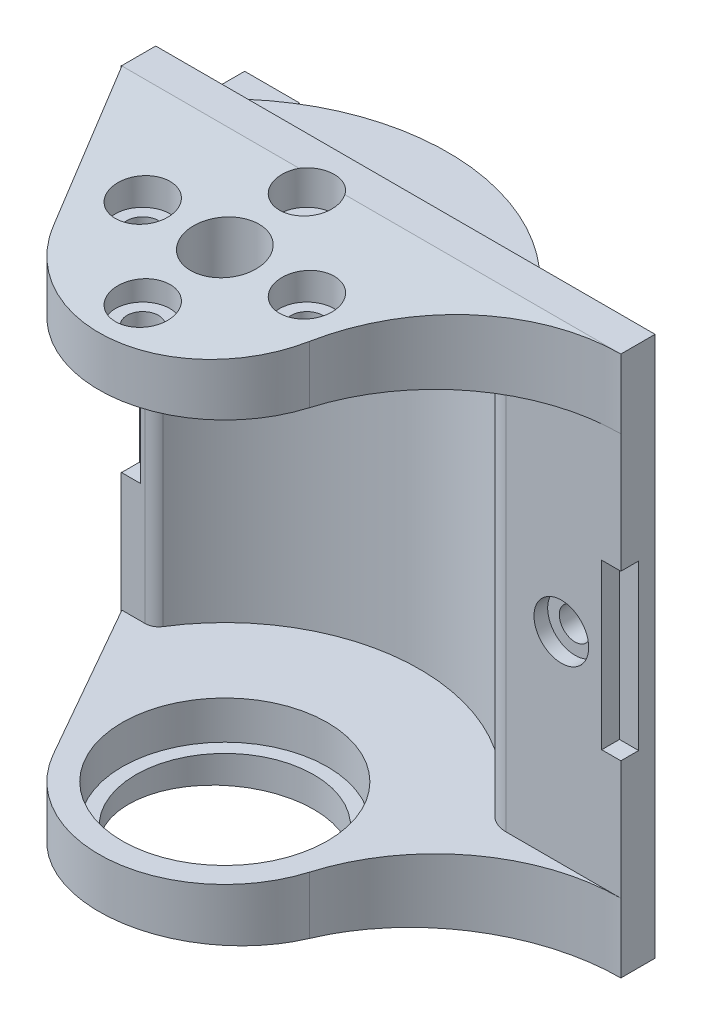
SolidWorks part; units mm, degrees
ref_plane "前视基准面" through (0, 0, 0) normal (0, 0, 1) x (1, 0, 0)
ref_plane "上视基准面" through (0, 0, 0) normal (0, 1, 0) x (1, 0, 0)
ref_plane "右视基准面" through (0, 0, 0) normal (1, 0, 0) x (0, 0, -1)
sketch "草图1" plane through (0, 0, 0) normal (0, 1, 0) x (1, 0, 0)
  circle A1 centre (0, 0) radius 16.3
  dimension "D1" = 32.6
extrude "凸台-拉伸1" add sketch "草图1" along normal mid plane 39.5
sketch "草图2" plane through (0, -19.75, 0) normal (0, -1, 0) x (1, 0, 0)
  line L1 (-14.65, -7.1) -> (21.85, -7.1)
  line L2 (-14.65, -7.1) -> (-14.65, -9.6)
  line L3 (-14.65, -9.6) -> (21.85, -9.6)
  line L4 (21.85, -7.1) -> (21.85, -9.6)
  dimension "D1" = 2.5
  dimension "D2" = 9.6
  dimension "D3" = 36.5
  dimension "D4" = 14.65
extrude "凸台-拉伸2" add sketch "草图2" against normal through all
sketch "草图3" plane through (0, -19.75, 0) normal (0, -1, 0) x (1, 0, 0)
  line L1 (21.85, -7.1) -> (-22.9944, -7.1)
  line L2 (21.85, -7.1) -> (21.85, 18.4067)
  line L3 (21.85, 18.4067) -> (-22.9944, 18.4067)
  line L4 (-22.9944, -7.1) -> (-22.9944, 18.4067)
extrude "切除-拉伸1" cut sketch "草图3" against normal blind 50
sketch "草图4" plane through (0, -19.75, 0) normal (0, -1, 0) x (1, 0, 0)
  line L0 (-14.65, -7.1462) -> (-7.9965, 4.5492)
  line L1 (21.85, -7.1) -> (21.85, 7.9567) construction
  line L2 (-14.65, -7.1462) -> (21.85, -7.1)
  arc A0 (8.8187, 2.6213) -> (-7.9965, 4.5492) centre (0, 0) ccw
  arc A1 (8.8187, 2.6213) -> (21.85, -7.1) centre (21.85, 6.4949) ccw
  dimension "D1" = 18.4
extrude "凸台-拉伸3" add sketch "草图4" against normal blind 5.05
mirror "镜向1" about plane through (0, 0, 0) normal (0, 1, 0) of "凸台-拉伸3"
sketch "草图5" plane through (0, -14.7, 0) normal (0, 1, 0) x (1, 0, 0)
  circle A0 centre (0, 0) radius 14.25
  dimension "D1" = 28.5
extrude "切除-拉伸2" cut sketch "草图5" along normal up to surface (29.4 mm away) up to face at (1.768, 14.7, -0.9093)
sketch "草图6" plane through (0, -14.7, 0) normal (0, 1, 0) x (1, 0, 0)
  circle A0 centre (0, 0) radius 7.5
  dimension "D1" = 15
extrude "切除-拉伸3" cut sketch "草图6" against normal through all
sketch "草图8" plane through (0, 19.75, 0) normal (0, 1, 0) x (1, 0, 0)
  circle A0 centre (0, -6) radius 1.15
  dimension "D1" = 2.3
  dimension "D2" = 6
extrude "切除-拉伸5" cut sketch "草图8" against normal up to surface (5.05 mm away) up to face at (1.1787, 14.7, -4.1645)
pattern_circular "阵列(圆周)1" count 4 over 360 about axis through (0, 0, 0) along (0, 1, 0) of "切除-拉伸5"
sketch "草图9" plane through (0, 19.75, 0) normal (0, 1, 0) x (1, 0, 0)
  circle A0 centre (0, 0) radius 2.5
  dimension "D1" = 5
extrude "切除-拉伸6" cut sketch "草图9" against normal up to next
sketch "草图10" plane through (0, 19.75, 0) normal (0, 1, 0) x (1, 0, 0)
  circle A0 centre (0, 6) radius 2
  circle A1 centre (6, 0) radius 2
  circle A2 centre (-6, 0) radius 2
  circle A3 centre (0, -6) radius 2
  dimension "D1" = 4
extrude "切除-拉伸7" cut sketch "草图10" against normal blind 2.5
sketch "草图11" plane through (0, -19.75, 0) normal (0, -1, 0) x (1, 0, 0)
  circle A0 centre (0, 0) radius 7.5
  circle A1 centre (0, 0) radius 6.5
  dimension "D1" = 13
extrude "凸台-拉伸4" add sketch "草图11" against normal blind 2.25
sketch "草图12" plane through (0, 0, -7.1) normal (0, 0, 1) x (1, 0, 0)
  line L0 (0, 0) -> (30.0134, 0) construction
  line L1 (21.85, 14.7) -> (21.85, -14.7) construction
  circle A0 centre (17.5, 0) radius 1.15
  dimension "D1" = 2.3
  dimension "D2" = 4.35
extrude "切除-拉伸9" cut sketch "草图12" against normal through all
sketch "草图13" plane through (0, 0, -7.1) normal (0, 0, 1) x (1, 0, 0)
  circle A0 centre (17.5, 0) radius 2
  dimension "D1" = 4
extrude "切除-拉伸10" cut sketch "草图13" against normal blind 1
sketch "草图14" plane through (0, 0, -7.1) normal (0, 0, 1) x (1, 0, 0)
  line L0 (21.85, 14.7) -> (21.85, -14.7) construction
  line L1 (20.45, -6) -> (23.25, -6)
  line L2 (20.45, -6) -> (20.45, 6)
  line L3 (20.45, 6) -> (23.25, 6)
  line L4 (23.25, -6) -> (23.25, 6)
  line L5 (20.45, -6) -> (23.25, 6) construction
  line L6 (20.45, 6) -> (23.25, -6) construction
  point P0 (21.85, 0)
  dimension "12" = 12
  dimension "D2" = 2.8
extrude "切除-拉伸11" cut sketch "草图14" against normal blind 1.3
sketch "草图15" plane through (0, 0, -7.1) normal (0, 0, 1) x (1, 0, 0)
  line L0 (0, 0) -> (-23.1213, 0) construction
  line L1 (-14.6724, -19.75) -> (-14.6724, 19.75) construction
  line L2 (-16.0724, -6) -> (-13.2724, -6)
  line L3 (-16.0724, -6) -> (-16.0724, 6)
  line L4 (-16.0724, 6) -> (-13.2724, 6)
  line L5 (-13.2724, -6) -> (-13.2724, 6)
  line L6 (-16.0724, -6) -> (-13.2724, 6) construction
  line L7 (-16.0724, 6) -> (-13.2724, -6) construction
  point P3 (-14.6724, 0)
  dimension "D1" = 12
  dimension "D2" = 2.8
extrude "切除-拉伸12" cut sketch "草图15" against normal blind 1.3
ref_plane "基准面1" through (0, 0, -15.1) normal (0, 0, -1) x (-1, 0, 0)
sketch "草图16" plane through (0, 0, -15.1) normal (0, 0, -1) x (-1, 0, 0)
  line L0 (14.65, 19.75) -> (14.65, -19.75) construction
  line L1 (9.65, 10.9) -> (13.65, 10.9)
  line L2 (9.65, 10.9) -> (9.65, 15.9)
  line L3 (9.65, 15.9) -> (13.65, 15.9)
  line L4 (13.65, 10.9) -> (13.65, 15.9)
  line L5 (9.65, 10.9) -> (13.65, 15.9) construction
  line L6 (9.65, 15.9) -> (13.65, 10.9) construction
  line L7 (0, 0) -> (27.535, 0) construction
  point P0 (11.65, 13.4)
  dimension "D1" = 1
  dimension "D2" = 10.9
  dimension "D3" = 5
  dimension "D4" = 4
extrude "凸台-拉伸5" add sketch "草图16" against normal up to surface (1.9635 mm away)
mirror "镜向4" about plane through (0, 0, 0) normal (0, 1, 0) of "凸台-拉伸5"
sketch "草图17" plane through (0, 0, -15.1) normal (0, 0, -1) x (-1, 0, 0)
  line L0 (11.65, 15.9) -> (11.65, 12.48) construction
  line L1 (13.65, 15.9) -> (9.65, 15.9) construction
  line L2 (13.65, 13.4) -> (11.1035, 13.4) construction
  line L3 (13.65, 10.9) -> (13.65, 15.9) construction
  line L5 (11.15, 12.4) -> (12.15, 12.4)
  line L6 (11.15, 12.4) -> (11.15, 14.4)
  line L7 (11.15, 14.4) -> (12.15, 14.4)
  line L8 (12.15, 12.4) -> (12.15, 14.4)
  line L9 (11.15, 12.4) -> (12.15, 14.4) construction
  line L10 (11.15, 14.4) -> (12.15, 12.4) construction
  point P8 (11.65, 13.4)
  dimension "D1" = 2
  dimension "D2" = 1
extrude "切除-拉伸13" cut sketch "草图17" against normal blind 2.5
mirror "镜向5" about plane through (0, 0, 0) normal (0, 1, 0) of "切除-拉伸13"
sketch "草图7" plane through (-14.65, 0, 0) normal (-1, 0, 0) x (0, 0, 1)
  line L0 (-7.1, 19.75) -> (9.2, 18.3239)
  line L1 (9.2, 14.7) -> (9.2, 19.75) construction
  line L2 (9.2, 18.3239) -> (9.2, 19.75)
  line L3 (9.2, 19.75) -> (-7.1, 19.75)
  dimension "D1" = 5
extrude "切除-拉伸8" cut sketch "草图7" against normal through all
mirror "镜向3" about plane through (0, 0, 0) normal (0, 1, 0) of "切除-拉伸8"
sketch "草图18" plane through (0, 0, -9.6) normal (0, 0, -1) x (-1, 0, 0)
  line L0 (-13.1731, 19.75) -> (-13.1731, -19.75) construction
  line L1 (13.1731, 19.75) -> (-13.1731, 19.75)
  line L2 (13.1731, 19.75) -> (13.1731, 17)
  line L3 (13.1731, 17) -> (-13.1731, 17)
  line L4 (-13.1731, 19.75) -> (-13.1731, 17)
  dimension "D1" = 2.75
extrude "切除-拉伸16" cut sketch "草图18" along normal blind 12.5
mirror "镜向6" about plane through (0, 0, 0) normal (0, 1, 0) of "切除-拉伸16"
fillet "圆角1" radius 2 1 edges at (12.3553, 0, -7.1)
fillet "圆角2" radius 1 1 edges at (-12.3553, 0, -7.1)
